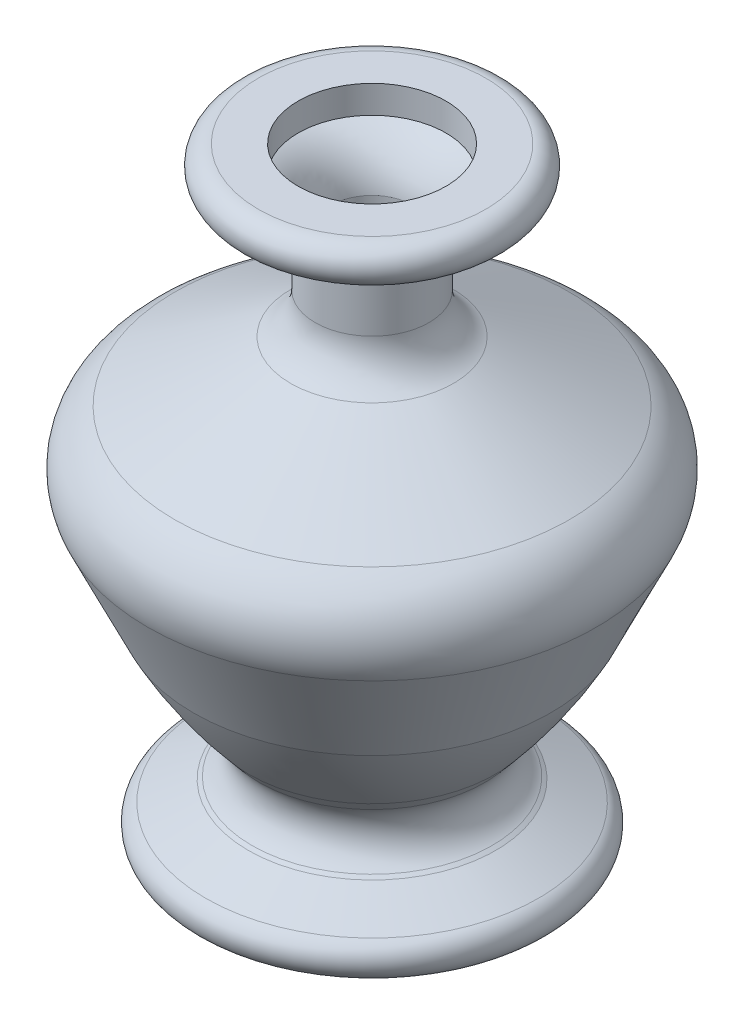
SolidWorks part; units mm, degrees
ref_plane "Front Plane" through (0, 0, 0) normal (0, 0, 1) x (1, 0, 0)
ref_plane "Top Plane" through (0, 0, 0) normal (0, 1, 0) x (1, 0, 0)
ref_plane "Right Plane" through (0, 0, 0) normal (1, 0, 0) x (0, 0, -1)
sketch "Sketch1" plane through (0, 0, 0) normal (0, 0, 1) x (1, 0, 0)
  line L0 (-60.0766, 168.7291) -> (-60.0766, -11.2449) construction
  line L1 (-66.4281, 6.7632) -> (-60.0766, 6.7632)
  line L11 (-75.0766, 147.0641) -> (-75.0766, 133.3641)
  line L13 (-69.3307, 40.8632) -> (-73.634, 40.8632) construction
  line L33 (-60.0766, 161.7632) -> (-79.5766, 161.7632) construction
  line L34 (-92.5783, 38.91) -> (-89.7696, 35.6022)
  line L35 (-73.634, 40.8632) -> (-107.1698, 60.2251) construction
  line L36 (-81.5521, 122.7114) -> (-112.1266, 106.8553)
  line L37 (-66.4281, 6.7632) -> (-101.8424, 6.7632)
  line L38 (-91.7444, 22.2185) -> (-92.7176, 21.5895)
  line L39 (-103.9734, 16.2863) -> (-92.7176, 21.5895)
  line L41 (-86.8539, 156.7632) -> (-90.0766, 156.7632)
  line L50 (-79.5766, 159.4601) -> (-79.5766, 166.7632)
  line L51 (-90.0766, 166.7632) -> (-79.5766, 166.7632)
  line L52 (-60.0766, 11.1632) -> (-60.0766, 6.7632)
  line L54 (-107.1698, 60.2251) -> (-119.2346, 85.8324)
  line L75 (-66.4281, 11.1632) -> (-60.0766, 11.1632)
  line L76 (-66.4281, 11.1632) -> (-101.8424, 11.1632)
  line L77 (-102.0981, 12.306) -> (-90.5761, 17.7345)
  line L78 (-89.3558, 18.5233) -> (-90.5761, 17.7345)
  line L79 (-89.2243, 41.7579) -> (-86.4156, 38.45)
  line L80 (-103.2428, 62.2135) -> (-115.2543, 87.7077)
  line L81 (-79.5264, 118.8054) -> (-110.101, 102.9494)
  line L82 (-70.6766, 147.4564) -> (-70.6766, 133.3641)
  arc A13 (-75.0766, 133.3641) -> (-81.5521, 122.7114) centre (-87.0766, 133.3641) cw
  arc A20 (-89.7696, 35.6022) -> (-91.7444, 22.2185) centre (-96.6302, 29.7769) cw
  arc A21 (-101.8424, 6.7632) -> (-103.9734, 16.2863) centre (-101.8424, 11.7632) cw
  arc A23 (-107.1698, 60.2251) -> (-92.5783, 38.91) centre (2.5544, 119.6863) ccw
  arc A24 (-90.0766, 166.7632) -> (-90.0766, 156.7632) centre (-90.0766, 161.7632) ccw
  arc A25 (-75.0766, 147.0641) -> (-86.8539, 156.7632) centre (-86.8539, 144.7632) ccw
  arc A33 (-119.2346, 85.8324) -> (-112.1266, 106.8553) centre (-104.7606, 92.6518) cw
  arc A34 (-70.6766, 147.4564) -> (-79.5766, 159.4601) centre (-86.8539, 144.7632) ccw
  arc A49 (-101.8424, 11.1632) -> (-102.0981, 12.306) centre (-101.8424, 11.7632) cw
  arc A50 (-86.4156, 38.45) -> (-89.3558, 18.5233) centre (-96.6302, 29.7769) cw
  arc A51 (-103.2428, 62.2135) -> (-89.2243, 41.7579) centre (2.5544, 119.6863) ccw
  arc A52 (-115.2543, 87.7077) -> (-110.101, 102.9494) centre (-104.7606, 92.6518) cw
  arc A53 (-70.6766, 133.3641) -> (-79.5264, 118.8054) centre (-87.0766, 133.3641) cw
  arc A54 (-70.6766, 147.4564) -> (-79.5766, 159.4601) centre (-86.8539, 144.7632) ccw
  arc A56 (-75.0168, 146.7339) -> (-83.9766, 156.4131) centre (-86.8539, 144.7632) ccw
  point P3 (0, 0)
  point P7 (-60.0766, 168.7291)
  point P10 (-60.0766, 168.7291)
  point P15 (-75.0766, 156.7632)
  point P16 (-87.7266, 28.4632)
  point P24 (-75.0766, 126.0696)
  point P26 (-95.0766, 161.7632)
  point P29 (-83.1324, 27.7853)
  point P36 (-60.0766, 161.7632)
  dimension "D1" = 34.1
  dimension "D3" = 12
  dimension "D5" = 5
  dimension "D9" = 8.9
  dimension "D11" = 15.5
  dimension "D12" = 124.8
  dimension "D7" = 13.7
  dimension "D8" = 11.2558
  dimension "D10" = 5
  dimension "D2" = 60
  dimension "D19" = 35
  dimension "D4" = 9
  dimension "D6" = 12
  dimension "D16" = 27.65
  dimension "D14" = 16
  dimension "D17" = 13.5575
  dimension "D18" = 21.7
revolve "Revolve4" add sketch "Sketch1" angle 360 about L0
